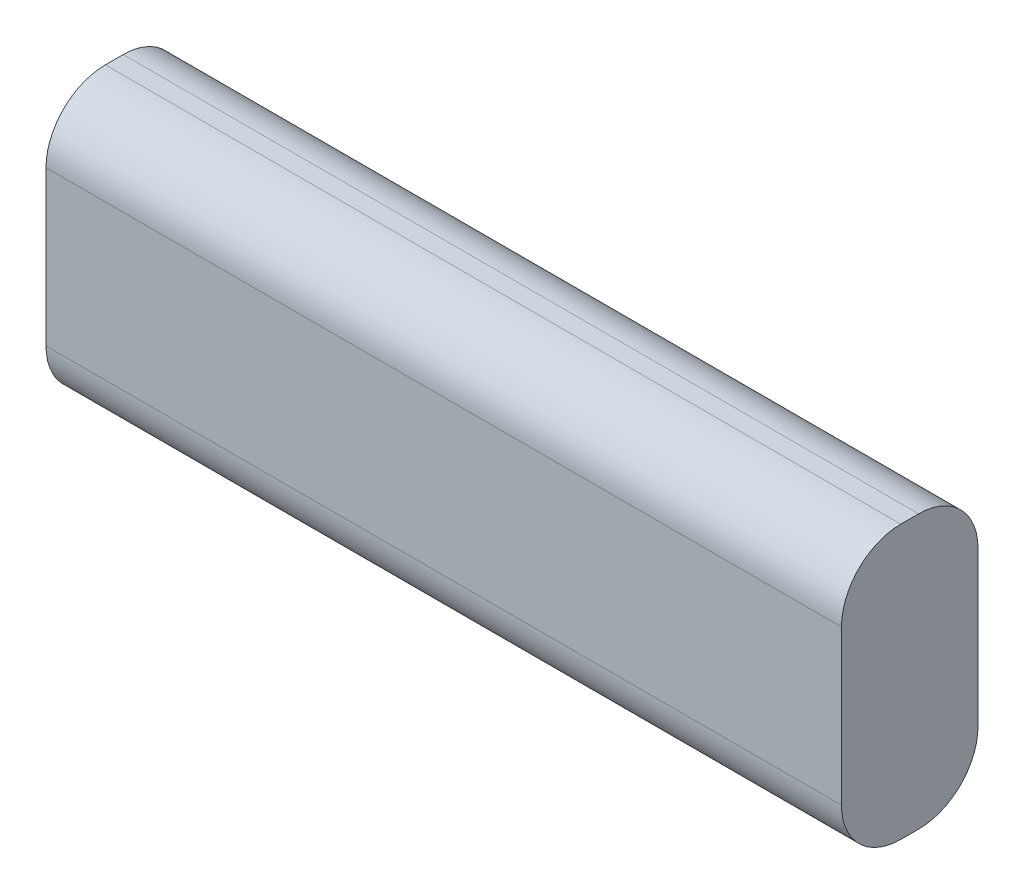
SolidWorks part; units mm, degrees
other "Markup1"
sketch "Sketch2" plane through (134, 46, 23) normal (0.3316, 0.541, 0.7729) x (0.943, -0.2145, -0.2545)
ref_plane "Front Plane" through (0, 0, 0) normal (0, 0, 1) x (1, 0, 0)
ref_plane "Top Plane" through (0, 0, 0) normal (0, 1, 0) x (1, 0, 0)
ref_plane "Right Plane" through (0, 0, 0) normal (1, 0, 0) x (0, 0, -1)
sketch "Sketch1" plane through (0, 0, 0) normal (0, 0, 1) x (1, 0, 0)
  line L1 (0, 0) -> (134, 0)
  line L2 (0, 0) -> (0, 46)
  line L3 (0, 46) -> (134, 46)
  line L4 (134, 0) -> (134, 46)
  dimension "D1" = 134
  dimension "D2" = 46
extrude "Boss-Extrude1" add sketch "Sketch1" along normal blind 23
fillet "Fillet4" radius 10 4 edges at (67, 46, 23) (67, 46, 0) (67, 0, 0) (67, 0, 23)
sketch "Sketch3" plane through (0, 0, 23) normal (0, 0, 1) x (1, 0, 0)
  text T0 "NiMH 7.2 V Battery" font "Century Schoolbook" height in points 24
